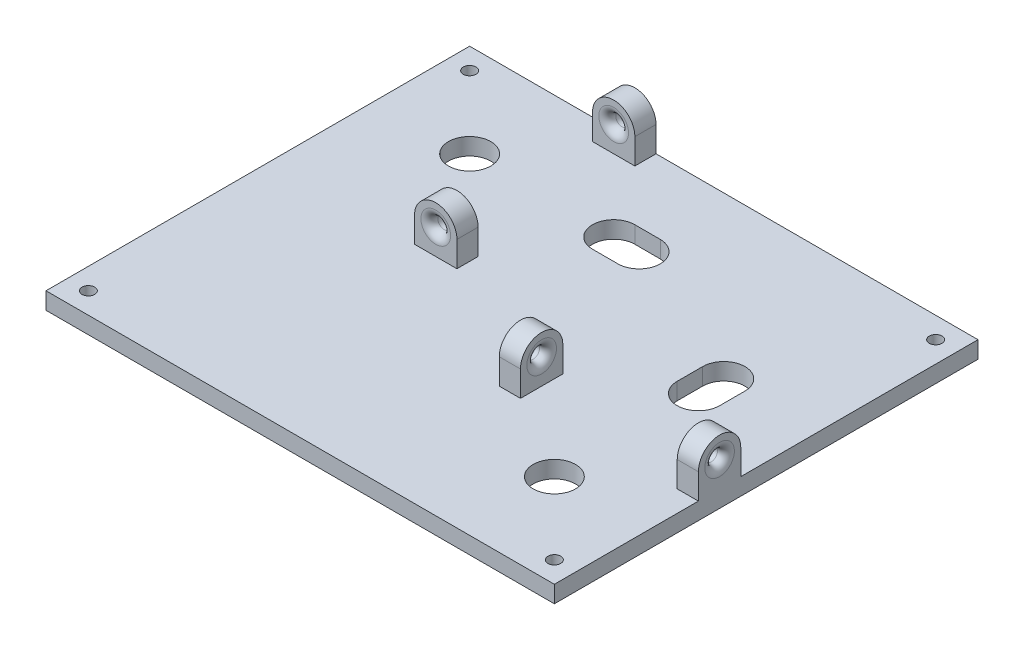
SolidWorks part; units mm, degrees
ref_plane "Front Plane" through (0, 0, 0) normal (0, 0, 1) x (1, 0, 0)
ref_plane "Top Plane" through (0, 0, 0) normal (0, 1, 0) x (1, 0, 0)
ref_plane "Right Plane" through (0, 0, 0) normal (1, 0, 0) x (0, 0, -1)
sketch "Sketch2" plane through (0, 0, 0) normal (0, 1, 0) x (1, 0, 0)
  line L1 (-60, 50) -> (60, 50)
  line L2 (-60, 50) -> (-60, -50)
  line L3 (-60, -50) -> (60, -50)
  line L4 (60, 50) -> (60, -50)
  line L5 (-60, 50) -> (60, -50) construction
  line L6 (-60, -50) -> (60, 50) construction
  point P0 (0, 0)
  dimension "D1" = 100
  dimension "D2" = 120
extrude "Boss-Extrude1" add sketch "Sketch2" along normal blind 4
sketch "Sketch3" plane through (0, 4, 0) normal (0, 1, 0) x (1, 0, 0)
  line L0 (60, -50) -> (60, 50) construction
  line L1 (-55, 45) -> (55, 45) construction
  line L2 (-55, 45) -> (-55, -45) construction
  line L3 (-55, -45) -> (55, -45) construction
  line L4 (55, 45) -> (55, -45) construction
  line L5 (-55, 45) -> (55, -45) construction
  line L6 (-55, -45) -> (55, 45) construction
  line L7 (-60, -50) -> (60, -50) construction
  circle A0 centre (-55, 45) radius 1.5
  circle A1 centre (55, 45) radius 1.5
  circle A2 centre (55, -45) radius 1.5
  circle A3 centre (-55, -45) radius 1.5
  point P0 (0, 0)
  dimension "D3" = 3
  dimension "D1" = 5
  dimension "D2" = 5
extrude "Cut-Extrude1" cut sketch "Sketch3" against normal blind 5
sketch "Sketch4" plane through (0, 4, 0) normal (0, 1, 0) x (1, 0, 0)
  line L0 (60, -50) -> (60, 50) construction
  line L1 (-60, -50) -> (60, -50) construction
  line L2 (60, 50) -> (-60, 50) construction
  line L4 (-60, 50) -> (-60, -50) construction
  circle A0 centre (-38, 28) radius 9.5 construction
  circle A1 centre (-4, 28) radius 9.5 construction
  circle A2 centre (38, 6) radius 9.5 construction
  circle A3 centre (38, -28) radius 9.5 construction
  circle A4 centre (-38, 28) radius 17 construction
  circle A5 centre (38, -28) radius 17 construction
  circle A6 centre (-38, 37.5) radius 1.65 construction
  circle A7 centre (-4, 37.5) radius 1.65 construction
  circle A8 centre (38, 15.5) radius 1.65 construction
  circle A9 centre (38, -18.5) radius 1.65 construction
  circle A10 centre (-28.5, 28) radius 1.65 construction
  circle A11 centre (-38, 18.5) radius 1.65 construction
  circle A12 centre (-47.5, 28) radius 1.65 construction
  circle A13 centre (5.5, 28) radius 1.65 construction
  circle A14 centre (-4, 18.5) radius 1.65 construction
  circle A15 centre (-13.5, 28) radius 1.65 construction
  circle A16 centre (47.5, 6) radius 1.65 construction
  circle A17 centre (38, -3.5) radius 1.65 construction
  circle A18 centre (28.5, 6) radius 1.65 construction
  circle A19 centre (47.5, -28) radius 1.65 construction
  circle A20 centre (38, -37.5) radius 1.65 construction
  circle A21 centre (28.5, -28) radius 1.65 construction
  circle A22 centre (-38, 28) radius 5
  circle A23 centre (-4, 28) radius 5
  circle A24 centre (38, 6) radius 5
  circle A25 centre (38, -28) radius 5
  dimension "D1" = 19
  dimension "D4" = 34
  dimension "D6" = 22
  dimension "D9" = 3.3
  dimension "D14" = 10
  dimension "D2" = 34
  dimension "D3" = 34
  dimension "D5" = 22
  dimension "D7" = 22
  dimension "D8" = 22
  dimension "D10" = 4
  dimension "D11" = 4
  dimension "D12" = 4
  dimension "D13" = 4
extrude "Cut-Extrude2" cut sketch "Sketch4" against normal blind 5
sketch "Sketch5" plane through (0, 4, 0) normal (0, 1, 0) x (1, 0, 0)
  line L0 (-4, 28) -> (2, 28) construction
  line L1 (-4, 33) -> (2, 33)
  line L2 (-4, 23) -> (2, 23)
  line L3 (38, 6) -> (38, 12) construction
  line L4 (33, 6) -> (33, 12)
  line L5 (43, 6) -> (43, 12)
  arc A0 (-4, 33) -> (-4, 23) centre (-4, 28) ccw
  arc A1 (2, 23) -> (2, 33) centre (2, 28) ccw
  arc A2 (33, 6) -> (43, 6) centre (38, 6) ccw
  arc A3 (43, 12) -> (33, 12) centre (38, 12) ccw
  circle A4 centre (38, 6) radius 5 construction
  point P3 (-1, 28)
  point P8 (38, 9)
  dimension "D1" = 6
extrude "Cut-Extrude3" cut sketch "Sketch5" against normal blind 10
sketch "Sketch6" plane through (0, 4, 0) normal (0, 1, 0) x (1, 0, 0)
  line L0 (-38, 28) -> (-4, 28) construction
  line L1 (38, -11) -> (55, -11) construction
  line L2 (38, 6) -> (38, -28) construction
  line L3 (-26, 8) -> (-16, 8)
  line L4 (60, -50) -> (60, 50) construction
  line L5 (55, -16) -> (60, -16)
  line L6 (55, -16) -> (55, -6)
  line L7 (55, -6) -> (60, -6)
  line L8 (60, -16) -> (60, -6)
  line L9 (-26, 50) -> (-16, 50)
  line L10 (-26, 50) -> (-26, 45)
  line L11 (-26, 45) -> (-16, 45)
  line L12 (-16, 50) -> (-16, 45)
  line L13 (60, 50) -> (-60, 50) construction
  line L14 (-26, 8) -> (-26, 3)
  line L15 (-26, 3) -> (-16, 3)
  line L16 (-16, 8) -> (-16, 3)
  line L17 (13, -6) -> (18, -6)
  line L18 (13, -6) -> (13, -16)
  line L19 (13, -16) -> (18, -16)
  line L20 (18, -6) -> (18, -16)
  line L21 (-21, 28) -> (-21, 45) construction
  point P32 (0, 0)
  dimension "D1" = 0
  dimension "D2" = 5
  dimension "D3" = 10
  dimension "D4" = 10
  dimension "D5" = 5
  dimension "D6" = 0
  dimension "D7" = 20
  dimension "D8" = 20
extrude "Boss-Extrude2" add sketch "Sketch6" along normal blind 15
sketch "Sketch7" plane through (0, 0, -3) normal (0, 0, 1) x (1, 0, 0)
  line L0 (-26, 19) -> (-16, 19) construction
  line L1 (-60, 4) -> (60, 4) construction
  line L2 (-26, 19) -> (-26, 4) construction
  line L3 (-16, 19) -> (-16, 4) construction
  line L8 (-26, 4) -> (-16, 4)
  line L9 (-16, 4) -> (-16, 19)
  line L10 (-16, 19) -> (-26, 19)
  line L11 (-26, 19) -> (-26, 4)
  line L13 (-16, 10) -> (-16, 19)
  line L14 (-16, 19) -> (-26, 19)
  line L15 (-26, 19) -> (-26, 10)
  circle A0 centre (-21, 10) radius 1.5
  arc A1 (-26, 10) -> (-16, 10) centre (-21, 10) cw
  point P4 (-21, 19)
  point P10 (0, 0)
  point P15 (-21, 7.52)
  point P16 (-21, 10.1452)
  dimension "D1" = 3
  dimension "D2" = 6
  dimension "D3" = 0
sketch "Sketch8" plane through (13, 0, -13) normal (-1, 0, 0) x (0, 0, 1)
  line L4 (-37, 4) -> (63, 4) construction
  line L13 (29, 10) -> (29, 19)
  line L14 (29, 19) -> (19, 19)
  line L15 (19, 19) -> (19, 10)
  circle A0 centre (24, 10) radius 1.5
  arc A1 (19, 10) -> (29, 10) centre (24, 10) cw
  point P2 (-14.804, 9.2481)
  point P3 (29, 19)
  point P4 (19, 19)
  point P5 (24.5132, 10.0856)
  point P10 (0, 0)
  point P15 (-21, 7.52)
  point P16 (-21, 10.1452)
  dimension "D1" = 3
  dimension "D2" = 6
extrude "Cut-Extrude4" cut sketch "Sketch7" against normal through all
extrude "Cut-Extrude5" cut sketch "Sketch8" against normal through all
fillet "Fillet1" radius 2 8 edges at (55, 10, 9.5) (60, 10, 12.5) (18, 10, 12.5) (-19.5, 10, -8) (-19.5, 10, -50) (-22.5, 10, -45) (13, 10, 12.5) (-19.5, 10, -3)
